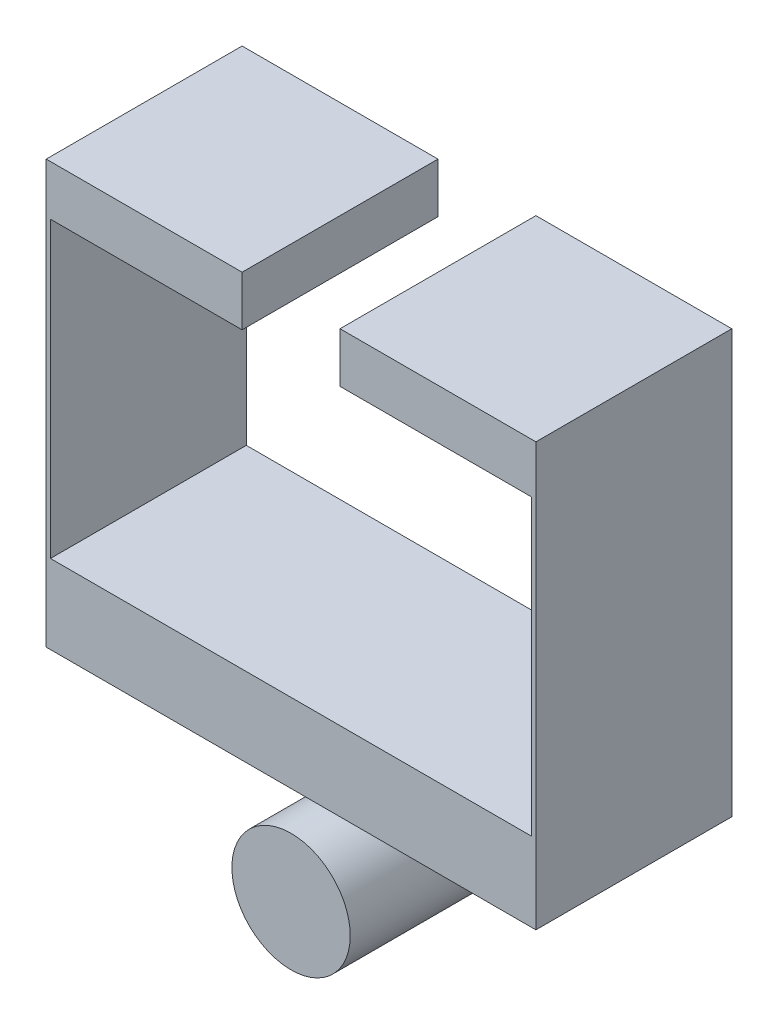
SolidWorks part; units mm, degrees
ref_plane "Front Plane" through (0, 0, 0) normal (0, 0, 1) x (1, 0, 0)
ref_plane "Top Plane" through (0, 0, 0) normal (0, 1, 0) x (1, 0, 0)
ref_plane "Right Plane" through (0, 0, 0) normal (1, 0, 0) x (0, 0, -1)
sketch "Sketch1" plane through (0, 0, 0) normal (0, 0, 1) x (1, 0, 0)
  circle A0 centre (0, 0) radius 7.6729
  dimension "D1" = 15.3457
extrude "Boss-Extrude1" add sketch "Sketch1" along normal blind 25.4
sketch "Sketch2" plane through (0, 0, 0) normal (0, 0, -1) x (-1, 0, 0)
  line L0 (7.6729, 0) -> (7.6729, 12.7)
  line L1 (7.6729, 12.7) -> (-7.6729, 12.7)
  line L2 (-7.6729, 12.7) -> (-7.6729, 0)
  line L3 (-7.6729, 0) -> (7.6729, 0)
  circle A1 centre (0, 0) radius 7.6729 construction
  dimension "D1" = 12.7
extrude "Boss-Extrude2" add sketch "Sketch2" against normal blind 1.8204
sketch "Sketch4" plane through (0, 0, 0) normal (0, 0, -1) x (-1, 0, 0)
  line L0 (-31.75, 12.7) -> (-31.75, 22.9352)
  line L2 (-31.75, 22.9352) -> (31.75, 22.9352)
  line L3 (31.75, 22.9352) -> (31.75, 12.7)
  line L4 (-31.75, 12.7) -> (-7.6729, 12.7)
  line L5 (7.6729, 12.7) -> (31.75, 12.7)
  line L6 (-7.6729, 12.7) -> (7.6729, 12.7)
  dimension "D1" = 63.5
  dimension "D2" = 10.2352
extrude "Boss-Extrude3" add sketch "Sketch4" against normal blind 25.4
sketch "Sketch5" plane through (0, 0, 0) normal (0, 0, -1) x (-1, 0, 0)
  line L0 (0, 0) -> (0, 44.2128) construction
  line L2 (31.75, 22.9352) -> (31.2001, 22.9352)
  line L3 (31.75, 22.9352) -> (31.75, 61.0352)
  line L4 (31.75, 61.0352) -> (31.2001, 61.0352)
  line L5 (31.2001, 22.9352) -> (31.2001, 61.0352)
  line L6 (-31.75, 22.9352) -> (-31.2001, 22.9352)
  line L7 (-31.75, 22.9352) -> (-31.75, 61.0352)
  line L8 (-31.75, 61.0352) -> (-31.2001, 61.0352)
  line L9 (-31.2001, 22.9352) -> (-31.2001, 61.0352)
  dimension "D1" = 38.1
  dimension "D2" = 0.5499
extrude "Boss-Extrude4" add sketch "Sketch5" against normal blind 25.4
sketch "Sketch6" plane through (0, 0, 0) normal (0, 0, -1) x (-1, 0, 0)
  line L1 (31.75, 61.0352) -> (6.35, 61.0352)
  line L2 (31.75, 61.0352) -> (31.75, 67.5085)
  line L3 (31.75, 67.5085) -> (6.35, 67.5085)
  line L4 (6.35, 61.0352) -> (6.35, 67.5085)
  line L5 (-31.75, 61.0352) -> (-6.35, 61.0352)
  line L6 (-31.75, 61.0352) -> (-31.75, 67.5085)
  line L7 (-31.75, 67.5085) -> (-6.35, 67.5085)
  line L8 (-6.35, 61.0352) -> (-6.35, 67.5085)
  dimension "D1" = 6.4733
  dimension "D2" = 25.4
extrude "Boss-Extrude5" add sketch "Sketch6" against normal blind 25.4
equation "\"SF\"= 4"
equation "\"W\"= 1300"
equation "\"F\" = 650"
equation "\"L1\"= 1in"
equation "\"SY\"= 120091"
equation "\"E\" = 16534300"
equation "\"z\"= ( \"SF\" * \"W\" * \"L1\" ) / ( 2 * \"SY\" )"
equation "\"r1\" = ( 4 * ( \"z\" / pi ) ) ^ ( 1 / 3 )"
equation "\"d1\"= 2 * \"r1\""
equation "\"L2\"= .5in"
equation "\"T2\"= ( \"W\" * \"SF\" ) / ( \"d1\" * \"SY\" )"
equation "\"L3\" = 2.5in"
equation "\"b3\"= 1in"
equation "\"T3\" = ( ( 1.5 * \"L3\" * \"W\" * \"SF\" ) / ( \"b3\" * \"SY\" ) ) ^ ( 1 / 2 )"
equation "\"T4\"= 1.5in"
equation "\"W4\"= 1in"
equation "\"L4\"= ( \"F\" * \"SF\" ) / ( \"W4\" * \"SY\" )"
equation "\"W5\"= 1in"
equation "\"L5\"= 1in"
equation "\"T5\"= ( ( 1.5 * \"W\" * \"L5\" * \"SF\" ) / ( \"W5\" * \"SY\" ) ) ^ ( 1 / 2 )"
equation "\"D1@Sketch1\"= \"d1\""
equation "\"D1@Boss-Extrude1\"=\"L1\""
equation "\"D1@Sketch2\"=\"L2\""
equation "\"D1@Boss-Extrude2\"= \"T2\""
equation "\"D1@Sketch4\"= \"L3\""
equation "\"D2@Sketch4\"= \"T3\""
equation "\"W3\"= 1in"
equation "\"D1@Boss-Extrude3\"=\"W3\""
equation "\"D1@Sketch5\"= \"T4\""
equation "\"D2@Sketch5\"= \"L4\""
equation "\"D1@Boss-Extrude4\"=\"W4\""
equation "\"D1@Sketch6\"= \"T5\""
equation "\"D2@Sketch6\"= \"L5\""
equation "\"D1@Boss-Extrude5\"= \"W5\""
